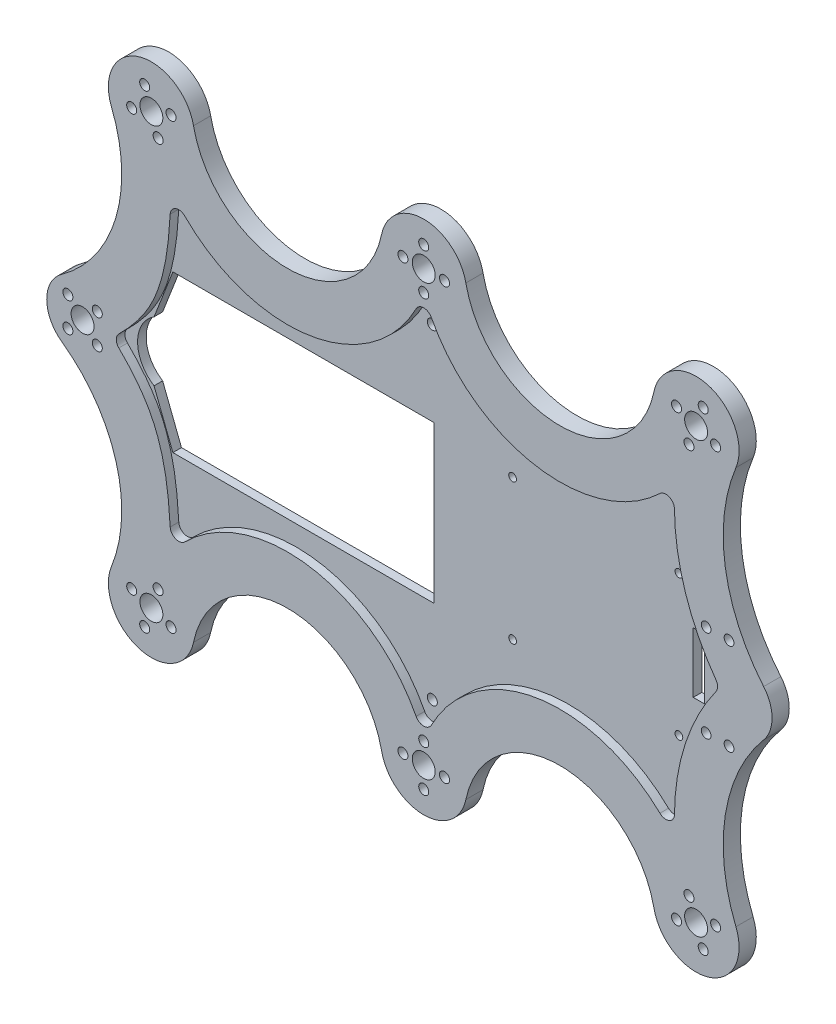
SolidWorks part; units mm, degrees
material "ABS"
ref_plane "Front Plane" through (0, 0, 0) normal (0, 0, 1) x (1, 0, 0)
ref_plane "Top Plane" through (0, 0, 0) normal (0, 1, 0) x (1, 0, 0)
ref_plane "Right Plane" through (0, 0, 0) normal (1, 0, 0) x (0, 0, -1)
sketch "Sketch2" plane through (0, 0, 0) normal (0, 0, 1) x (1, 0, 0)
  line L1 (-179.5726, -184.2704) -> (73.4274, -184.2704) construction
  arc A0 (70.4888, -192.3221) -> (70.4888, -176.2186) centre (60.9274, -184.2704) ccw construction
  arc A1 (70.4888, -192.3221) -> (70.4888, -176.2186) centre (60.9274, -184.2704) ccw
  arc A2 (70.4888, -192.3221) -> (60.8186, -253.6104) centre (116.3833, -230.9704) ccw
  arc A3 (70.4888, -192.3221) -> (56.3833, -230.9704) centre (116.3833, -230.9704) ccw construction
  arc A5 (32.2367, -262.3006) -> (-33.3819, -262.3006) centre (-0.5726, -269.0683) ccw
  arc A7 (-62.7633, -262.3006) -> (-128.3819, -262.3006) centre (-95.5726, -269.0683) ccw
  arc A9 (-156.9984, -253.6962) -> (-174.3417, -194.4395) centre (-203.4179, -235.1159) ccw
  arc A10 (-174.3417, -174.1012) -> (-174.3417, -194.4395) centre (-167.0726, -184.2704) ccw
  arc A11 (-156.9984, -253.6962) -> (-128.3819, -262.3006) centre (-143.0726, -259.2704) ccw
  arc A12 (-62.7633, -262.3006) -> (-33.3819, -262.3006) centre (-48.0726, -259.2704) ccw
  arc A13 (32.2367, -262.3006) -> (60.8186, -253.6104) centre (46.9274, -259.2704) ccw
  arc A14 (32.2367, -106.2401) -> (60.8186, -114.9303) centre (46.9274, -109.2704) cw
  arc A15 (-62.7633, -106.2401) -> (-33.3819, -106.2401) centre (-48.0726, -109.2704) cw
  arc A16 (-156.9984, -114.8445) -> (-128.3819, -106.2401) centre (-143.0726, -109.2704) cw
  arc A17 (-156.9984, -114.8445) -> (-174.3417, -174.1012) centre (-203.4179, -133.4248) cw
  arc A18 (-62.7633, -106.2401) -> (-128.3819, -106.2401) centre (-95.5726, -99.4724) cw
  arc A19 (32.2367, -106.2401) -> (-33.3819, -106.2401) centre (-0.5726, -99.4724) cw
  arc A20 (70.4888, -176.2186) -> (60.8186, -114.9303) centre (116.3833, -137.5703) cw
extrude "Boss-Extrude1" add sketch "Sketch2" along normal blind 6 contours A1 A20 A14 A19 A15 A18 A16 A17 A10 A9 A11 A7 A12 A5 A13 A2
sketch "Sketch3" plane through (0, 0, 6) normal (0, 0, 1) x (1, 0, 0)
  circle A0 centre (-167.0726, -184.2704) radius 2.2
  circle A1 centre (-143.0726, -259.2704) radius 2.2
  circle A2 centre (-48.0726, -259.2704) radius 2.2
  circle A3 centre (46.9274, -259.2704) radius 2.2
  circle A4 centre (-67.0726, -160.1004) radius 1.75
  circle A5 centre (-67.0726, -208.4404) radius 1.75
  circle A6 centre (15.5574, -208.4404) radius 1.75
  circle A7 centre (8.0574, -160.1004) radius 1.75
  circle A8 centre (50.4274, -168.2704) radius 1.7
  circle A9 centre (50.4274, -200.2704) radius 1.7
  circle A10 centre (58.4274, -200.2704) radius 1.7
  circle A11 centre (58.4274, -168.2704) radius 1.7
  circle A12 centre (46.9274, -109.2704) radius 2.2
  arc A13 (49.1274, -109.2704) -> (44.7274, -109.2704) centre (46.9274, -109.2704) ccw construction
  circle A14 centre (-48.0726, -109.2704) radius 2.2
  circle A15 centre (-143.0726, -109.2704) radius 2.2
extrude "Cut-Extrude1" cut sketch "Sketch3" against normal through all
sketch "Sketch4" plane through (0, 0, 6) normal (0, 0, 1) x (1, 0, 0)
  line L0 (-179.5726, -184.2704) -> (73.4274, -184.2704) construction
  line L1 (-48.0726, -247.4512) -> (-48.0726, -94.2704) construction
  circle A0 centre (-48.0726, -259.2704) radius 4
  circle A1 centre (-40.8226, -259.2704) radius 1.75
  circle A2 centre (-48.0726, -266.5204) radius 1.75
  circle A3 centre (-55.3226, -259.2704) radius 1.75
  circle A4 centre (-48.0726, -252.0204) radius 1.75
  circle A5 centre (46.9274, -259.2704) radius 4
  circle A6 centre (53.738, -256.7847) radius 1.75
  circle A7 centre (49.4131, -266.0809) radius 1.75
  circle A8 centre (40.1168, -261.756) radius 1.75
  circle A9 centre (44.4418, -252.4598) radius 1.75
  circle A10 centre (-143.0726, -259.2704) radius 4
  circle A11 centre (-140.7251, -252.4109) radius 1.75
  circle A12 centre (-136.2132, -261.6178) radius 1.75
  circle A13 centre (-145.4201, -266.1298) radius 1.75
  circle A14 centre (-149.932, -256.9229) radius 1.75
  arc A15 (-174.3417, -174.1012) -> (-174.3417, -194.4395) centre (-167.0726, -184.2704) ccw construction
  arc A16 (70.4888, -192.3221) -> (70.4888, -176.2186) centre (60.9274, -184.2704) ccw construction
  circle A17 centre (-149.932, -111.6178) radius 1.75
  circle A18 centre (-145.4201, -102.4109) radius 1.75
  circle A19 centre (-136.2132, -106.9229) radius 1.75
  circle A20 centre (-140.7251, -116.1298) radius 1.75
  circle A21 centre (-143.0726, -109.2704) radius 4
  circle A22 centre (44.4418, -116.0809) radius 1.75
  circle A23 centre (40.1168, -106.7847) radius 1.75
  circle A24 centre (49.4131, -102.4598) radius 1.75
  circle A25 centre (53.738, -111.756) radius 1.75
  circle A26 centre (46.9274, -109.2704) radius 4
  circle A27 centre (-48.0726, -116.5204) radius 1.75
  circle A28 centre (-55.3226, -109.2704) radius 1.75
  circle A29 centre (-48.0726, -102.0204) radius 1.75
  circle A30 centre (-40.8226, -109.2704) radius 1.75
  circle A31 centre (-48.0726, -109.2704) radius 4
  circle A32 centre (-167.0726, -184.2704) radius 4
  circle A33 centre (-161.9461, -179.1438) radius 1.75
  circle A34 centre (-161.9461, -189.3969) radius 1.75
  circle A35 centre (-172.1991, -189.3969) radius 1.75
  circle A36 centre (-172.1991, -179.1438) radius 1.75
  arc A51 (-33.3819, -106.2401) -> (-62.7633, -106.2401) centre (-48.0726, -109.2704) ccw construction
  arc A59 (34.0057, -228.2444) -> (-42.1143, -235.3557) centre (-0.5726, -269.0683) ccw
  arc A60 (-45.999, -236.0307) -> (-42.1143, -235.3557) centre (-44.4437, -233.4653) ccw construction
  arc A61 (34.0057, -228.2444) -> (36.4735, -227.1711) centre (34.9752, -227.0998) ccw
  arc A62 (34.0057, -228.2444) -> (36.4735, -227.1711) centre (34.9752, -227.0998) ccw construction
  arc A63 (36.4735, -227.1711) -> (50.8192, -185.1299) centre (116.3833, -230.9704) cw
  arc A64 (50.8192, -185.1299) -> (36.4735, -227.1711) centre (116.3833, -230.9704) ccw construction
  arc A65 (-42.1143, -235.3557) -> (-45.999, -236.0307) centre (-44.4437, -233.4653) cw
  arc A66 (-54.0309, -235.3557) -> (-50.1462, -236.0307) centre (-51.7015, -233.4653) ccw
  arc A67 (-54.0309, -235.3557) -> (-50.1462, -236.0307) centre (-51.7015, -233.4653) ccw construction
  arc A68 (-45.999, -236.0307) -> (-50.1462, -236.0307) centre (-48.0726, -239.4512) ccw
  arc A69 (-54.0309, -235.3557) -> (-131.2223, -229.1766) centre (-95.5726, -269.0683) ccw
  arc A70 (-133.7179, -228.1654) -> (-131.2223, -229.1766) centre (-132.2218, -228.0581) ccw construction
  arc A71 (-131.2223, -229.1766) -> (-133.7179, -228.1654) centre (-132.2218, -228.0581) cw
  arc A72 (-54.0309, -235.3557) -> (-131.2223, -229.1766) centre (-95.5726, -269.0683) ccw construction
  arc A73 (50.8192, -185.1299) -> (50.8192, -183.4108) centre (49.5899, -184.2704) ccw
  arc A74 (51.0899, -184.2704) -> (50.8192, -183.4108) centre (49.5899, -184.2704) ccw construction
  arc A75 (36.4735, -141.3696) -> (50.8192, -183.4108) centre (116.3833, -137.5703) ccw construction
  arc A76 (-151.254, -185.3226) -> (-151.2605, -183.2178) centre (-150.1884, -184.2669) cw
  arc A77 (-151.2605, -183.2178) -> (-151.254, -185.3226) centre (-150.1884, -184.2669) ccw construction
  arc A78 (-45.999, -236.0307) -> (-50.1462, -236.0307) centre (-48.0726, -239.4512) ccw construction
  arc A79 (34.0057, -140.2963) -> (-42.1143, -133.185) centre (-0.5726, -99.4724) cw
  arc A80 (-42.1143, -133.185) -> (-45.999, -132.51) centre (-44.4437, -135.0754) ccw
  arc A81 (-45.999, -132.51) -> (-50.1462, -132.51) centre (-48.0726, -129.0895) cw
  arc A82 (-54.0309, -133.185) -> (-50.1462, -132.51) centre (-51.7015, -135.0754) cw
  arc A83 (-54.0309, -133.185) -> (-131.2223, -139.3641) centre (-95.5726, -99.4724) cw
  arc A84 (-151.254, -183.2181) -> (-151.2605, -185.3229) centre (-150.1884, -184.2738) ccw
  arc A85 (-131.2223, -139.3641) -> (-133.7179, -140.3753) centre (-132.2218, -140.4826) ccw
  arc A86 (36.4735, -141.3696) -> (50.8192, -183.4108) centre (116.3833, -137.5703) ccw
  arc A87 (34.0057, -140.2963) -> (36.4735, -141.3696) centre (34.9752, -141.4409) cw
  spline S1 degree 3 poles (-133.7179, -228.1654) (-134.1501, -223.9447) (-134.8901, -218.5114) (-136.4659, -211.2857) (-137.8285, -206.2986) (-140.1812, -199.8596) (-143.4984, -194.1473) (-147.5333, -189.1757) (-149.9433, -186.6454) (-151.254, -185.3226) knots 0 0 0 0 0.268528 0.346252 0.467778 0.595363 0.779092 0.882175 1 1 1 1
  spline S3 degree 3 poles (-151.254, -185.3226) (-150.075, -186.5126) (-148.9193, -187.7208) (-146.3752, -190.5803) (-145.0207, -192.2582) (-143.1787, -194.9232) (-142.5959, -195.836) (-141.7736, -197.2457) (-141.5081, -197.7223) (-140.9948, -198.6894) (-140.7467, -199.1804) (-139.5623, -201.6463) (-138.7813, -203.6714) (-137.4206, -207.7849) (-136.8431, -209.8739) (-136.0859, -213.0418) (-135.8521, -214.1036) (-135.4171, -216.2375) (-135.216, -217.31) (-134.6592, -220.5305) (-134.3485, -222.685) (-133.9668, -225.9274) (-133.8538, -227.0099) (-133.7531, -228.1353) (-133.7494, -228.1762) (-133.7458, -228.217) knots 0 0 0 0 0.105841 0.105841 0.243007 0.243007 0.311589 0.311589 0.345881 0.345881 0.380172 0.380172 0.517338 0.517338 0.654503 0.654503 0.723086 0.723086 0.791668 0.791668 0.928834 0.928834 0.997416 0.997416 1 1 1 1 weights 1 1 1 1 1 1 1 1 1 1 1 1 1 1 1 1 1 1 1 1 1 1 1 1 1 1 construction
  spline S4 degree 3 poles (-133.7179, -140.3753) (-134.1501, -144.596) (-134.8901, -150.0293) (-136.4659, -157.255) (-137.8285, -162.2421) (-140.1812, -168.6811) (-143.4984, -174.3934) (-147.5333, -179.365) (-149.9433, -181.8953) (-151.254, -183.2181) knots 0 0 0 0 0.268528 0.346252 0.467778 0.595363 0.779092 0.882175 1 1 1 1
  circle M3 centre (-167.0726, -184.2704) radius 2.2
  circle M4 centre (-143.0726, -109.2704) radius 2.2
  circle M5 centre (-48.0726, -109.2704) radius 2.2
  circle M6 centre (46.9274, -109.2704) radius 2.2
  circle M7 centre (58.4274, -168.2704) radius 1.7
  circle M8 centre (58.4274, -200.2704) radius 1.7
  circle M9 centre (50.4274, -200.2704) radius 1.7
  circle M10 centre (-67.0726, -160.1004) radius 1.75
  circle M11 centre (46.9274, -259.2704) radius 2.2
  circle M12 centre (-48.0726, -259.2704) radius 2.2
  circle M13 centre (-143.0726, -259.2704) radius 2.2
  circle M14 centre (-67.0726, -208.4404) radius 1.75
  circle M15 centre (15.5574, -208.4404) radius 1.75
  circle M16 centre (8.0574, -160.1004) radius 1.75
  circle M17 centre (50.4274, -168.2704) radius 1.7
extrude "Cut-Extrude2" cut sketch "Sketch4" against normal through all contours A85 S4 A84 A76 S1 A71 A69 A66 A68 A65 A59 A61 A63 A73 A86 A87 A79 A80 A81 A82 A83 M10 M14 M16 M15 | A31 M5 | A30 | A27 | A28 | A29 | A26 M6 | A25 | A24 | A23 | A22 | M9 | M8 | M17 | M7 | A7 | M11 | A6 | A9 | A8 | A0 M12 | A1 | A4 | A3 | A2 | M13 | A13 | A12 | A14 | A11 | A32 M3 | A34 | A35 | A36 | A33 | M4 | A19 | A20 | A17 | A18 | A5 | A10 | A21
sketch "Sketch7" plane through (0, 0, 6) normal (0, 0, 1) x (1, 0, 0)
  line L0 (-151.6884, -184.2704) -> (51.0899, -184.2704) construction
  arc A0 (-42.1143, -235.3557) -> (34.0057, -228.2444) centre (-0.5726, -269.0683) cw
  arc A1 (34.0057, -228.2444) -> (-42.1143, -235.3557) centre (-0.5726, -269.0683) ccw construction
  arc A2 (34.0057, -228.2444) -> (36.4735, -227.1711) centre (34.9752, -227.0998) ccw construction
  arc A3 (34.0057, -228.2444) -> (36.4735, -227.1711) centre (34.9752, -227.0998) ccw
  arc A4 (50.8192, -185.1299) -> (36.4735, -227.1711) centre (116.3833, -230.9704) ccw construction
  arc A5 (-42.1143, -235.3557) -> (-45.999, -236.0307) centre (-44.4437, -233.4653) cw
  arc A6 (-44.0726, -239.4512) -> (-45.999, -236.0307) centre (-48.0726, -239.4512) ccw construction
  arc A7 (-45.999, -236.0307) -> (-50.1462, -236.0307) centre (-48.0726, -239.4512) ccw
  arc A8 (-45.999, -236.0307) -> (-50.1462, -236.0307) centre (-48.0726, -239.4512) ccw construction
  arc A9 (-50.1462, -236.0307) -> (-54.0309, -235.3557) centre (-51.7015, -233.4653) cw
  arc A10 (-54.0309, -235.3557) -> (-131.2223, -229.1766) centre (-95.5726, -269.0683) ccw construction
  arc A11 (-54.0309, -235.3557) -> (-131.2223, -229.1766) centre (-95.5726, -269.0683) ccw
  arc A12 (-133.7179, -228.1654) -> (-131.2223, -229.1766) centre (-132.2218, -228.0581) ccw construction
  arc A13 (-131.2223, -229.1766) -> (-133.6628, -228.4745) centre (-132.2218, -228.0581) cw
  arc A14 (-151.2539, -183.218) -> (-151.2559, -185.3138) centre (-150.1884, -184.2669) ccw
  arc A15 (-151.254, -183.2181) -> (-151.6884, -184.2704) centre (-150.1884, -184.2738) ccw construction
  arc A16 (36.4735, -227.1711) -> (50.8192, -185.1299) centre (116.3833, -230.9704) cw
  arc A17 (50.8192, -185.1299) -> (50.8192, -183.4108) centre (49.5899, -184.2704) ccw
  arc A18 (36.4735, -141.3696) -> (50.8192, -183.4108) centre (116.3833, -137.5703) ccw construction
  arc A19 (36.4735, -141.3696) -> (50.8192, -183.4108) centre (116.3833, -137.5703) ccw
  arc A20 (-151.2539, -185.3227) -> (-151.2559, -183.2269) centre (-150.1884, -184.2738) cw
  arc A21 (-131.2223, -139.3641) -> (-133.6628, -140.0662) centre (-132.2218, -140.4826) ccw
  arc A22 (-54.0309, -133.185) -> (-131.2223, -139.3641) centre (-95.5726, -99.4724) cw
  arc A23 (-50.1462, -132.51) -> (-54.0309, -133.185) centre (-51.7015, -135.0754) ccw
  arc A24 (-45.999, -132.51) -> (-50.1462, -132.51) centre (-48.0726, -129.0895) cw
  arc A25 (-42.1143, -133.185) -> (-45.999, -132.51) centre (-44.4437, -135.0754) ccw
  arc A26 (34.0057, -140.2963) -> (36.4735, -141.3696) centre (34.9752, -141.4409) cw
  arc A27 (-42.1143, -133.185) -> (34.0057, -140.2963) centre (-0.5726, -99.4724) ccw
  arc A28 (-50.7361, -122.7091) -> (-131.3912, -135.0712) centre (-95.5726, -99.4724) cw
  arc A29 (-131.3912, -135.0712) -> (-136.5147, -137.0248) centre (-133.519, -137.186) ccw construction
  arc A30 (-131.3912, -135.0712) -> (-136.5147, -137.0248) centre (-133.519, -137.186) ccw
  arc A31 (-154.4189, -182.1404) -> (-154.4189, -186.4004) centre (-152.3062, -184.2704) ccw
  arc A32 (-154.4189, -182.1404) -> (-154.4189, -186.4004) centre (-152.3062, -184.2704) ccw construction
  arc A33 (-50.7361, -122.7091) -> (-45.409, -122.7091) centre (-48.0726, -124.0895) cw
  arc A34 (-45.409, -122.7091) -> (-50.7361, -122.7091) centre (-48.0726, -124.0895) ccw construction
  arc A35 (-45.409, -122.7091) -> (34.313, -135.986) centre (-0.5726, -99.4724) ccw
  arc A36 (39.3853, -138.1332) -> (34.313, -135.986) centre (36.3854, -138.1552) ccw construction
  arc A37 (34.313, -135.986) -> (39.3853, -138.1332) centre (36.3854, -138.1552) cw
  arc A38 (39.3853, -138.1332) -> (53.8645, -182.5191) centre (116.3833, -137.5703) ccw construction
  arc A39 (39.3853, -138.1332) -> (53.8645, -182.5191) centre (116.3833, -137.5703) ccw
  arc A40 (53.8645, -182.5191) -> (53.8645, -186.0216) centre (51.4287, -184.2704) cw
  arc A41 (53.8645, -186.0216) -> (39.3853, -230.4075) centre (116.3833, -230.9704) ccw construction
  arc A42 (-45.409, -122.7091) -> (34.313, -135.986) centre (-0.5726, -99.4724) ccw construction
  arc A43 (39.3853, -230.4075) -> (53.8645, -186.0216) centre (116.3833, -230.9704) cw
  arc A44 (34.313, -232.5547) -> (39.3853, -230.4075) centre (36.3854, -230.3855) ccw
  arc A45 (-45.409, -245.8316) -> (34.313, -232.5547) centre (-0.5726, -269.0683) cw
  arc A46 (-50.7361, -245.8316) -> (-45.409, -245.8316) centre (-48.0726, -244.4512) ccw
  arc A47 (-131.3912, -233.4695) -> (-136.5147, -231.5159) centre (-133.519, -231.3547) cw
  arc A48 (-50.7361, -245.8316) -> (-131.3912, -233.4695) centre (-95.5726, -269.0683) ccw
  arc A49 (-42.1143, -235.3557) -> (34.0057, -228.2444) centre (-0.5726, -269.0683) cw
  arc A50 (34.0057, -228.2444) -> (36.4735, -227.1711) centre (34.9752, -227.0998) ccw
  arc A51 (-42.1143, -235.3557) -> (-45.999, -236.0307) centre (-44.4437, -233.4653) cw
  arc A52 (-45.999, -236.0307) -> (-50.1462, -236.0307) centre (-48.0726, -239.4512) ccw
  arc A53 (-50.1462, -236.0307) -> (-54.0309, -235.3557) centre (-51.7015, -233.4653) cw
  arc A54 (-54.0309, -235.3557) -> (-131.2223, -229.1766) centre (-95.5726, -269.0683) ccw
  arc A55 (-131.2223, -229.1766) -> (-133.6628, -228.4745) centre (-132.2218, -228.0581) cw
  arc A56 (-151.2539, -183.218) -> (-151.2559, -185.3138) centre (-150.1884, -184.2669) ccw
  arc A57 (36.4735, -227.1711) -> (50.8192, -185.1299) centre (116.3833, -230.9704) cw
  arc A58 (-151.2539, -185.3227) -> (-151.2559, -183.2269) centre (-150.1884, -184.2738) cw
  circle A59 centre (-48.0726, -127.5895) radius 1.75
  circle A60 centre (-48.0726, -240.9512) radius 1.75
  spline S0 degree 3 poles (-133.7179, -140.3753) (-134.1501, -144.596) (-134.8901, -150.0293) (-136.4659, -157.255) (-137.8285, -162.2421) (-140.1812, -168.6811) (-143.4984, -174.3934) (-147.5333, -179.365) (-149.9433, -181.8953) (-151.254, -183.2181) knots 0 0 0 0 0.268528 0.346252 0.467778 0.595363 0.779092 0.882175 1 1 1 1 construction
  spline S1 degree 3 poles (-133.6628, -228.4745) (-134.027, -225.1771) (-134.7835, -219.0921) (-136.5804, -210.5056) (-138.8648, -203.0045) (-143.1255, -194.1386) (-147.8996, -188.6765) (-151.2559, -185.3138) knots 0 0 0 0 0.208544 0.385067 0.55077 0.700225 1 1 1 1
  spline S2 degree 3 poles (-133.7179, -228.1654) (-134.1501, -223.9447) (-134.8901, -218.5114) (-136.4659, -211.2857) (-137.8285, -206.2986) (-140.1812, -199.8596) (-143.4984, -194.1473) (-147.5333, -189.1757) (-149.9433, -186.6454) (-151.254, -185.3226) knots 0 0 0 0 0.268528 0.346252 0.467778 0.595363 0.779092 0.882175 1 1 1 1 construction
  spline S3 degree 3 poles (-133.6628, -140.0662) (-134.027, -143.3636) (-134.7835, -149.4486) (-136.5804, -158.0351) (-138.8648, -165.5362) (-143.1255, -174.4021) (-147.8996, -179.8642) (-151.2559, -183.2269) knots 0 0 0 0 0.208544 0.385067 0.55077 0.700225 1 1 1 1
  spline S4 degree 3 poles (-136.5147, -137.0248) (-137.0961, -147.8286) (-139.4357, -164.7551) (-149.6517, -177.4121) (-154.4189, -182.1404) knots 0 0 0 0 0.623296 1 1 1 1 weights 1 1 1 1 1 construction
  spline S5 degree 3 poles (-136.5147, -137.0248) (-136.6876, -140.2282) (-137.0993, -145.5255) (-138.4472, -154.277) (-140.501, -161.9446) (-144.0439, -169.468) (-148.4889, -175.9059) (-152.2527, -179.9913) (-154.4189, -182.1404) knots 0 0 0 0 0.192811 0.318882 0.531899 0.666883 0.816628 1 1 1 1
  spline S6 degree 3 poles (-136.5147, -231.5159) (-136.6876, -228.3125) (-137.0993, -223.0152) (-138.4472, -214.2637) (-140.501, -206.5961) (-144.0439, -199.0727) (-148.4889, -192.6348) (-152.2527, -188.5494) (-154.4189, -186.4004) knots 0 0 0 0 0.192811 0.318882 0.531899 0.666883 0.816628 1 1 1 1
  spline S7 degree 3 poles (-133.6628, -228.4745) (-134.027, -225.1771) (-134.7835, -219.0921) (-136.5804, -210.5056) (-138.8648, -203.0045) (-143.1255, -194.1386) (-147.8996, -188.6765) (-151.2559, -185.3138) knots 0 0 0 0 0.208544 0.385067 0.55077 0.700225 1 1 1 1
extrude "Cut-Extrude3" cut sketch "Sketch7" against normal blind 3
sketch "Sketch8" plane through (0, 0, 6) normal (0, 0, 1) x (1, 0, 0)
  circle A0 centre (-48.0726, -240.9512) radius 1.75
  circle A1 centre (-48.0726, -127.5895) radius 1.75
extrude "Cut-Extrude4" cut sketch "Sketch8" against normal through all
sketch "Sketch9" plane through (0, 0, 3) normal (0, 0, 1) x (1, 0, 0)
  line L0 (-133.7179, -228.1654) -> (-151.254, -185.3226)
  line L1 (-151.254, -185.3226) -> (-152.7636, -183.4475)
  line L2 (-152.7636, -183.4475) -> (-134.3174, -138.093)
  line L3 (-134.3174, -138.093) -> (-41.0499, -131.0105)
  line L4 (-41.0499, -131.0105) -> (36.977, -138.093)
  line L5 (36.977, -138.093) -> (52.5512, -183.4475)
  line L6 (52.5512, -183.4475) -> (36.977, -231.2875)
  line L7 (36.977, -231.2875) -> (-43.9757, -237.4349)
  line L8 (-43.9757, -237.4349) -> (-133.519, -231.3547)
  line L9 (-133.519, -231.3547) -> (-133.7179, -228.1654)
extrude "Boss-Extrude2" add sketch "Sketch9" against normal up to surface (3 mm away) up to face at (-46.3226, -240.9512, 0)
sketch "Sketch12" plane through (0, 0, 3) normal (0, 0, 1) x (1, 0, 0)
  line L1 (-138.5726, -156.9704) -> (-70.5726, -156.9704)
  line L2 (-138.5726, -156.9704) -> (-138.5726, -211.5704)
  line L3 (-138.5726, -211.5704) -> (-70.5726, -211.5704)
  line L4 (-70.5726, -156.9704) -> (-70.5726, -211.5704)
  circle A0 centre (-167.0726, -184.2704) radius 4 construction
  dimension "D4" = 27.3
  dimension "D1" = 68
  dimension "D2" = 54.6
  dimension "D3" = 28.5
extrude "Cut-Extrude5" cut sketch "Sketch12" against normal through all
sketch "Sketch13" plane through (0, 0, 3) normal (0, 0, 1) x (1, 0, 0)
  line L0 (-138.5726, -211.5704) -> (-70.5726, -211.5704) construction
  line L1 (-70.5726, -156.9704) -> (-56.5726, -156.9704)
  line L2 (-70.5726, -156.9704) -> (-70.5726, -211.5704)
  line L3 (-70.5726, -211.5704) -> (-56.5726, -211.5704)
  line L4 (-56.5726, -156.9704) -> (-56.5726, -211.5704)
  line L5 (-70.5726, -156.9704) -> (-138.5726, -156.9704) construction
  line L6 (-70.5726, -211.5704) -> (-70.5726, -156.9704) construction
  dimension "D1" = 14
  dimension "D2" = 0
extrude "Cut-Extrude6" cut sketch "Sketch13" against normal through all
sketch "Sketch14" plane through (0, 0, 3) normal (0, 0, 1) x (1, 0, 0)
  line L1 (42.9274, -173.7704) -> (46.9274, -173.7704)
  line L2 (42.9274, -173.7704) -> (42.9274, -194.7704)
  line L3 (42.9274, -194.7704) -> (46.9274, -194.7704)
  line L4 (46.9274, -173.7704) -> (46.9274, -194.7704)
  arc A0 (70.4888, -192.3221) -> (70.4888, -176.2186) centre (60.9274, -184.2704) ccw construction
  dimension "D1" = 21
  dimension "D2" = 4
  dimension "D3" = 14
  dimension "D4" = 10.5
extrude "Cut-Extrude7" cut sketch "Sketch14" against normal through all
sketch "Sketch15" plane through (0, 0, 3) normal (0, 0, 1) x (1, 0, 0)
  line L0 (42.9274, -173.7704) -> (42.9274, -194.7704) construction
  circle A0 centre (37.9274, -159.7704) radius 1.35
  circle A1 centre (37.9274, -208.7704) radius 1.35
  circle A2 centre (-20.0742, -208.7704) radius 1.35
  circle A3 centre (-20.0742, -159.7704) radius 1.35
  point P10 (0, 0)
  dimension "D1" = 5
  dimension "D2" = 5
  dimension "D3" = 58.0016
extrude "Cut-Extrude8" cut sketch "Sketch15" against normal through all
sketch "Sketch16" plane through (0, 0, 3) normal (0, 0, 1) x (1, 0, 0)
  line L0 (-56.5726, -156.9704) -> (-138.5726, -156.9704) construction
  line L1 (-56.5726, -211.5704) -> (-47.5626, -211.5704)
  line L2 (-56.5726, -211.5704) -> (-56.5726, -156.9704)
  line L3 (-56.5726, -156.9704) -> (-47.5626, -156.9704)
  line L4 (-47.5626, -211.5704) -> (-47.5626, -156.9704)
extrude "Cut-Extrude9" cut sketch "Sketch16" against normal through all
sketch "Sketch17" plane through (0, 0, 3) normal (0, 0, 1) x (1, 0, 0)
  line L0 (-138.5726, -156.9704) -> (-138.5726, -211.5704) construction
  line L1 (-138.5726, -171.9626) -> (-138.5726, -196.5781)
  arc A0 (-138.5726, -196.5781) -> (-138.5726, -171.9626) centre (-138.5726, -184.2704) cw
extrude "Cut-Extrude10" cut sketch "Sketch17" against normal blind 10
sketch "Sketch18" plane through (0, 0, 3) normal (0, 0, 1) x (1, 0, 0)
  line L0 (-138.5726, -211.5704) -> (-145.1414, -194.6786)
  line L1 (-145.1414, -194.6786) -> (-138.5726, -194.6786)
  line L2 (-138.5726, -194.6786) -> (-138.5726, -211.5704)
  line L3 (-150.8803, -184.2704) -> (-47.5626, -184.2704) construction
  line L4 (-47.5626, -211.5704) -> (-47.5626, -156.9704) construction
  line L5 (-138.5726, -173.8621) -> (-138.5726, -156.9704)
  line L6 (-145.1414, -173.8621) -> (-138.5726, -173.8621)
  line L7 (-138.5726, -156.9704) -> (-145.1414, -173.8621)
  arc A0 (-138.5726, -171.9626) -> (-138.5726, -196.5781) centre (-138.5726, -184.2704) ccw construction
extrude "Cut-Extrude11" cut sketch "Sketch18" against normal blind 10
